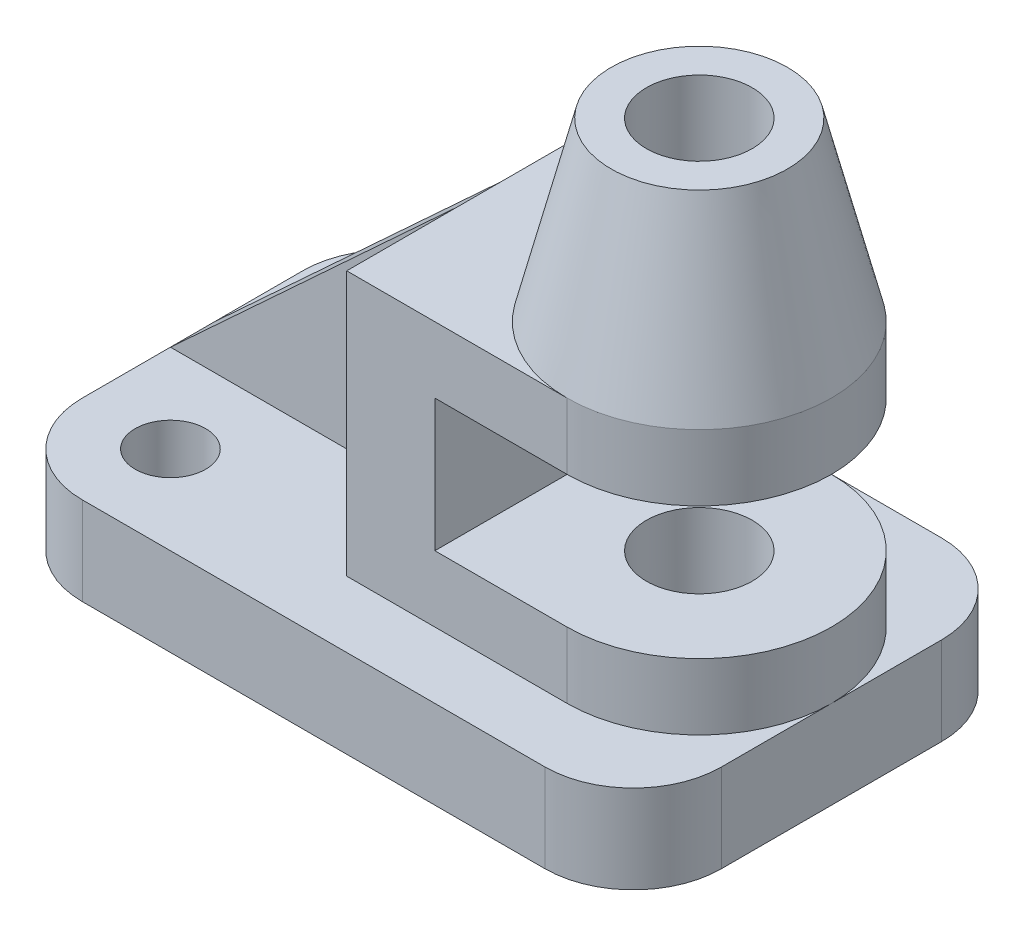
SolidWorks part; units mm, degrees
ref_plane "Front Plane" through (0, 0, 0) normal (0, 0, 1) x (1, 0, 0)
ref_plane "Top Plane" through (0, 0, 0) normal (0, 1, 0) x (1, 0, 0)
ref_plane "Right Plane" through (0, 0, 0) normal (1, 0, 0) x (0, 0, -1)
sketch "Sketch3" plane through (0, 0, 0) normal (0, 0, 1) x (1, 0, 0)
  line L0 (-59.8818, -31.7866) -> (85.1182, -31.7866)
  line L1 (85.1182, -31.7866) -> (85.1182, -11.7866)
  line L2 (85.1182, -11.7866) -> (-59.8818, -11.7866)
  line L3 (-59.8818, -11.7866) -> (-59.8818, -31.7866)
extrude "Boss-Extrude3" add sketch "Sketch3" along normal mid plane 90 contours L3 L0 L1 L2
sketch "Sketch4" plane through (0, -11.7866, 0) normal (0, 1, 0) x (1, 0, 0)
  line L0 (-59.8818, 5) -> (-59.8818, -5)
  line L2 (-59.8818, -5) -> (5.1182, -5)
  line L3 (-59.8818, 5) -> (5.1182, 5)
  line L4 (5.1182, 0) -> (5.1182, 30)
  line L5 (5.1182, 0) -> (5.1182, -30)
  line L6 (5.1182, 30) -> (55.1182, 30)
  line L7 (5.1182, -30) -> (55.1182, -30)
  arc A0 (55.1182, -30) -> (55.1182, 30) centre (55.1182, 0) ccw
  line M9 (-59.8818, 45) -> (-59.8818, -45)
extrude "Boss-Extrude6" add sketch "Sketch4" along normal blind 60 contours L5 L4 L3 L2 M9 | L7 A0 L6 L4 L5
sketch "Sketch7" plane through (0, 0, 5) normal (0, 0, 1) x (1, 0, 0)
  line L0 (-59.8818, -11.7866) -> (5.1182, 48.2134)
extrude "Cut-Extrude6" cut sketch "Sketch7" against normal blind 10 and the other way through all
sketch "Sketch10" plane through (0, 0, 30) normal (0, 0, 1) x (1, 0, 0)
  line L3 (25.1182, 3.2134) -> (85.1182, 3.2134)
  line L4 (85.1182, -11.7866) -> (85.1182, 48.2134) construction
  line L5 (85.1182, 3.2134) -> (85.1182, 33.2134)
  line L6 (85.1182, 33.2134) -> (25.1182, 33.2134)
  line L7 (25.1182, 33.2134) -> (25.1182, 3.2134)
  dimension "D3" = 30
extrude "Cut-Extrude7" cut sketch "Sketch10" against normal blind 90
sketch "Sketch11" plane through (0, 3.2134, 0) normal (0, 1, 0) x (1, 0, 0)
  circle A0 centre (55.1182, 0) radius 12
extrude "Cut-Extrude9" cut sketch "Sketch11" against normal blind 59 and the other way blind 84
sketch "Sketch13" plane through (0, 0, 0) normal (0, 0, 1) x (1, 0, 0)
  line L0 (55.1182, 48.2134) -> (55.1182, 88.2134)
  line L1 (55.1182, 88.2134) -> (35.1182, 88.2134)
  line L2 (55.1182, 48.2134) -> (25.1182, 48.2134)
  line L3 (5.1182, 48.2134) -> (55.1182, 48.2134) construction
  line L4 (25.1182, 48.2134) -> (35.1182, 88.2134)
  dimension "D1" = 40
  dimension "D2" = 20
  dimension "D3" = 30
revolve "Revolve1" add sketch "Sketch13" angle 360 about L0
sketch "Sketch15" plane through (0, 88.2134, 0) normal (0, 1, 0) x (1, 0, 0)
  circle A0 centre (55.1182, 0) radius 12
  dimension "D1" = 24
extrude "Cut-Extrude10" cut sketch "Sketch15" against normal blind 40
sketch "Sketch16" plane through (0, -11.7866, 0) normal (0, 1, 0) x (1, 0, 0)
  circle A0 centre (-39.8818, -25) radius 8
  circle A1 centre (-39.8818, 25) radius 8
extrude "Cut-Extrude11" cut sketch "Sketch16" against normal blind 40
fillet "Fillet1" radius 20 1 edges at (-59.8818, -21.7866, 45)
fillet "Fillet2" radius 20 1 edges at (-59.8818, -21.7866, -45)
fillet "Fillet3" radius 20 1 edges at (85.1182, -21.7866, -45)
fillet "Fillet4" radius 20 1 edges at (85.1182, -21.7866, 45)
